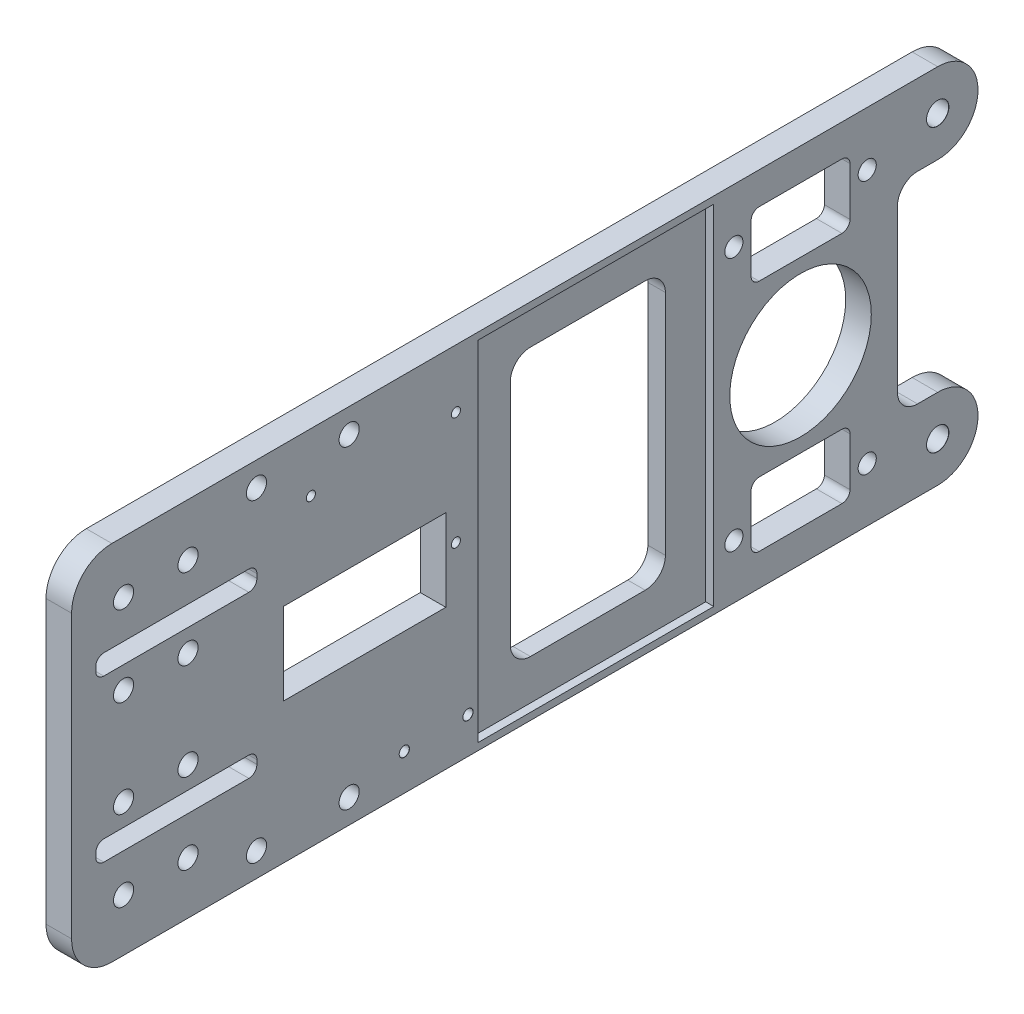
SolidWorks part; units mm, degrees
other "Chassis"
other "Bearing Plate"
other "IMU"
other "Bearing Plate 2"
material "Nylon 101"
ref_plane "Front Plane" through (0, 0, 0) normal (1, 0, 0) x (0, 1, 0)
ref_plane "Top Plane" through (0, 0, 0) normal (0, 0, 1) x (0, 1, 0)
ref_plane "Right Plane" through (0, 0, 0) normal (0, 1, 0) x (-1, 0, 0)
sketch "Sketch1" plane through (0, 0, 0) normal (1, 0, 0) x (0, 1, 0)
  line L0 (-45, 121.55) -> (-45, -44.05)
  line L1 (-45, -44.05) -> (45, -44.05)
  line L2 (45, -44.05) -> (45, 121.55)
  line L5 (0, 180.95) -> (0, 0) construction
  line L6 (-45, 121.55) -> (0, 121.55) construction
  line L7 (0, 121.55) -> (45, 121.55) construction
  line L8 (-448.1018, -246.5596) -> (346.2414, -246.5596) construction
  line L9 (0, 77.55) -> (0, 121.55) construction
  line L10 (-40.75, 77.55) -> (40.75, 77.55)
  line L11 (-40.75, 77.55) -> (-40.75, 24.05)
  line L12 (-40.75, 24.05) -> (40.75, 24.05)
  line L13 (40.75, 77.55) -> (40.75, 24.05)
  line L14 (-35, -34.05) -> (35, -34.05) construction
  line L15 (-35, -24.05) -> (35, -24.05)
  line L16 (-35, -44.05) -> (35, -44.05)
  line L17 (0, -34.05) -> (0, 0) construction
  line L18 (-36, 98.35) -> (-36, 82.55) construction
  line L19 (-33.525, 100.825) -> (-33.525, 80.075)
  line L20 (-33.525, 100.825) -> (-49.025, 100.825)
  line L21 (-49.025, 100.825) -> (-49.025, 80.075)
  line L22 (-33.525, 80.075) -> (-49.025, 80.075)
  line L23 (-36, 90.45) -> (-49.025, 90.45) construction
  line L24 (-36, 100.825) -> (-36, 98.35) construction
  line L25 (-36, 98.35) -> (-33.525, 98.35) construction
  line L26 (-33.525, 80.075) -> (-33.525, 77.55) construction
  line L27 (0, 103.55) -> (2.5, 103.55) construction
  line L36 (0, 124.55) -> (33, 124.55)
  line L37 (0, 124.55) -> (0, 82.55)
  line L38 (0, 82.55) -> (33, 82.55)
  line L39 (33, 124.55) -> (33, 82.55)
  line L40 (2.5, 121.55) -> (30.5, 121.55) construction
  line L41 (2.5, 121.55) -> (2.5, 85.55) construction
  line L42 (2.5, 85.55) -> (30.5, 85.55) construction
  line L43 (30.5, 121.55) -> (30.5, 85.55) construction
  line L44 (16.5, 121.55) -> (16.5, 124.55) construction
  line L45 (-45, 180.95) -> (-45, 121.55)
  line L46 (0, 180.95) -> (-45, 180.95)
  line L47 (0, 180.95) -> (45, 180.95)
  line L48 (45, 180.95) -> (45, 121.55)
  circle A0 centre (0, 0) radius 6.35 construction
  circle A1 centre (0, 0) radius 17.4625 construction
  circle A2 centre (0, 0) radius 19.05 construction
  circle A3 centre (0, 0) radius 17.5641
  arc A4 (-35, -24.05) -> (-35, -44.05) centre (-35, -34.05) ccw
  arc A5 (35, -44.05) -> (35, -24.05) centre (35, -34.05) ccw
  circle A6 centre (-36, 98.35) radius 1.5
  circle A7 centre (-36, 82.55) radius 1.5
  point P22 (0, -34.05)
  dimension "D5" = 12.7
  dimension "D6" = 34.925
  dimension "D8" = 38.1
  dimension "D9" = 0.1016
  dimension "D10" = 35.1282
  dimension "D14" = 10
  dimension "D3" = 5
  dimension "D15" = 5
  dimension "D18" = 3
  dimension "D20" = 7.5
  dimension "D25" = 28
  dimension "D27" = 5
  dimension "D28" = 12
  dimension "D29" = 5
  dimension "D4" = 90
  dimension "D7" = 246.5596
  dimension "D11" = 81.5
  dimension "D12" = 53.5
  dimension "D16" = 15.5
  dimension "D17" = 20.75
  dimension "D19" = 15.8
  dimension "D22" = 225
  dimension "D23" = 33
  dimension "D24" = 42
  dimension "D26" = 36
extrude "Boss-Extrude1" add sketch "Sketch1" along normal mid plane 6.35
sketch "Sketch2" plane through (3.175, 0, 0) normal (1, 0, 0) x (0, 1, 0)
  line L0 (-39.05, 0) -> (-19.05, 0) construction
  line L1 (-39.05, 21.55) -> (39.05, 21.55)
  line L2 (-39.05, 21.55) -> (-39.05, -21.55)
  line L3 (-39.05, -21.55) -> (39.05, -21.55)
  line L4 (39.05, 21.55) -> (39.05, -21.55)
  line L5 (19.05, 0) -> (39.05, 0) construction
  line L6 (-31.55, 16.55) -> (31.55, 16.55) construction
  line L7 (31.55, 16.55) -> (31.55, -16.55) construction
  line L8 (31.55, -16.55) -> (-31.55, -16.55) construction
  line L9 (-31.55, -16.55) -> (-31.55, 16.55) construction
  line L10 (0, 16.55) -> (0, 21.55) construction
  line L11 (31.55, 0) -> (39.05, 0) construction
  line L12 (-31.55, 24.05) -> (-31.55, 16.55) construction
  line L13 (-31.55, 16.55) -> (-39.05, 16.55) construction
  line L14 (-40.75, 24.05) -> (40.75, 24.05) construction
  circle A1 centre (0, 0) radius 19.05 construction
  circle A2 centre (-31.55, 16.55) radius 2 construction
  circle A3 centre (-31.55, -16.55) radius 2 construction
  circle A4 centre (31.55, 16.55) radius 2 construction
  circle A5 centre (31.55, -16.55) radius 2 construction
  dimension "D1" = 20
  dimension "D3" = 4
  dimension "D2" = 7.5
  dimension "D4" = 2.5
extrude "Boss-Extrude2" add sketch "Sketch2" along normal blind 8.7312 separate body
sketch "Sketch3" plane through (11.9062, 0, 0) normal (1, 0, 0) x (0, 1, 0)
  circle A0 centre (0, 0) radius 17.5641 construction
  circle A1 centre (0, 0) radius 17.5641
hole_wizard "M4 Clearance Hole2" positions "Sketch22" profile "Sketch23" hole size "M4" standard "ANSI Metric" end condition through all
sketch "Sketch22" plane through (11.9062, 0, 0) normal (1, 0, 0) x (0, 1, 0)
  point P0 (-31.55, 16.55)
  point P3 (-31.55, -16.55)
  point P6 (31.55, -16.55)
  point P9 (31.55, 16.55)
sketch "Sketch23" plane through (11.9062, -31.55, 16.55) normal (0, 1, 0) x (0, 0, -1)
  line L0 (0, 0) -> (0, 15.0813)
  line L1 (0, 15.0813) -> (2.25, 15.0813)
  line L2 (2.25, 15.0813) -> (2.25, 0.025)
  line L3 (2.25, 0.025) -> (2.275, 0)
  line L5 (2.275, 0) -> (0, 0)
  line L6 (-2.25, 0.025) -> (-2.275, 0) construction
  line L11 (0, -6.35) -> (0, 107.95) construction
  dimension "Thru Hole Dia." = 4.5
  dimension "Thru Hole Depth" = 15.0813
  dimension "Near C'Sink Dia." = 4.55
  dimension "Near C'Sink Angle" = 90
sketch "Sketch24" plane through (-3.175, 0, 0) normal (-1, 0, 0) x (0, -1, 0)
  line L0 (39.05, 21.55) -> (39.05, -21.55) construction
  line L1 (39.05, -21.55) -> (-39.05, -21.55) construction
  line L2 (-39.05, 21.55) -> (-39.05, -21.55) construction
  line L3 (39.05, 21.55) -> (-39.05, 21.55) construction
  line L4 (39.05, 21.55) -> (39.05, -21.55)
  line L5 (39.05, -21.55) -> (-39.05, -21.55)
  line L6 (-39.05, 21.55) -> (-39.05, -21.55)
  line L7 (39.05, 21.55) -> (-39.05, 21.55)
extrude "Boss-Extrude3" add sketch "Sketch24" along normal blind 8.7312 separate body
hole_wizard "Tap Drill for M4x0.7 Tap1" positions "Sketch25" profile "Sketch27" hole size "M4x0.7" standard "ANSI Metric"
sketch "Sketch25" plane through (-11.9062, 0, 0) normal (-1, 0, 0) x (0, -1, 0)
  point P0 (-31.55, 16.55)
  point P2 (-31.55, -16.55)
  point P4 (31.55, -16.55)
  point P6 (31.55, 16.55)
sketch "Sketch27" plane through (-11.9062, 31.55, 16.55) normal (0, 1, 0) x (0, 0, 1)
  line L0 (0, 0) -> (0, 9.7227)
  line L1 (0, 9.7227) -> (1.65, 8.7312)
  line L2 (1.65, 8.7312) -> (1.65, 0.025)
  line L3 (1.65, 0.025) -> (1.675, 0)
  line L5 (1.675, 0) -> (0, 0)
  line L6 (-1.65, 0.025) -> (-1.675, 0) construction
  line L10 (0, 9.7227) -> (-1.65, 8.7312) construction
  line L11 (0, -6.35) -> (0, 107.95) construction
  dimension "Hole Dia." = 3.3
  dimension "Hole Depth" = 8.7312
  dimension "Near C'Sink Dia." = 3.35
  dimension "Near C'Sink Angle" = 90
  dimension "Drill Angle" = 118
hole_wizard "Tap Drill for M3x0.5 Tap1" positions "Sketch9" profile "Sketch10" hole size "M3x0.5" standard "ANSI Metric" end condition through all
sketch "Sketch9" plane through (3.175, 0, 0) normal (1, 0, 0) x (0, 1, 0)
  point P0 (-36, 98.35)
  point P3 (-36, 82.55)
sketch "Sketch10" plane through (3.175, -36, 98.35) normal (0, 1, 0) x (0, 0, -1)
  line L0 (0, 0) -> (0, 15.0813)
  line L1 (0, 15.0813) -> (1.25, 15.0813)
  line L2 (1.25, 15.0813) -> (1.25, 0.025)
  line L3 (1.25, 0.025) -> (1.275, 0)
  line L5 (1.275, 0) -> (0, 0)
  line L6 (-1.25, 0.025) -> (-1.275, 0) construction
  line L11 (0, -6.35) -> (0, 107.95) construction
  dimension "Thru Hole Dia." = 2.5
  dimension "Thru Hole Depth" = 15.0813
  dimension "Near C'Sink Dia." = 2.55
  dimension "Near C'Sink Angle" = 90
extrude "Cut-Extrude3" cut sketch "Sketch3" against normal through all
hole_wizard "M5 Clearance Hole1" positions "Sketch13" profile "Sketch12" hole size "M5" standard "ANSI Metric" end condition through all
sketch "Sketch13" plane through (3.175, 0, 0) normal (1, 0, 0) x (0, 1, 0)
  point P0 (-35, -34.05)
  point P3 (35, -34.05)
sketch "Sketch12" plane through (3.175, -35, -34.05) normal (0, 1, 0) x (0, 0, -1)
  line L0 (0, 0) -> (0, 15.0813)
  line L1 (0, 15.0813) -> (2.75, 15.0813)
  line L2 (2.75, 15.0813) -> (2.75, 0.025)
  line L3 (2.75, 0.025) -> (2.775, 0)
  line L5 (2.775, 0) -> (0, 0)
  line L6 (-2.75, 0.025) -> (-2.775, 0) construction
  line L11 (0, -6.35) -> (0, 107.95) construction
  dimension "Thru Hole Dia." = 5.5
  dimension "Thru Hole Depth" = 15.0813
  dimension "Near C'Sink Dia." = 5.55
  dimension "Near C'Sink Angle" = 90
sketch "Sketch14" plane through (3.175, 0, 0) normal (1, 0, 0) x (0, 1, 0)
  line L8 (43.25, 21.55) -> (43.25, 80.05)
  line L9 (-43.25, 21.55) -> (43.25, 21.55)
  line L10 (-43.25, 80.05) -> (-43.25, 21.55)
  line L11 (43.25, 80.05) -> (-43.25, 80.05)
  line L12 (43.25, 21.55) -> (43.25, 80.05)
  line L13 (-43.25, 21.55) -> (43.25, 21.55)
  line L14 (-43.25, 80.05) -> (-43.25, 21.55)
  line L15 (43.25, 80.05) -> (-43.25, 80.05)
  dimension "D1" = 2.5
extrude "Cut-Extrude4" cut sketch "Sketch14" against normal blind 2
fillet "Fillet4" radius 10 4 edges at (0, 45, -44.05) (0, -45, -44.05) (0, 45, 180.95) (0, -45, 180.95)
fillet "Fillet5" radius 5 4 edges at (-7.5406, -39.05, 21.55) (-7.5406, -39.05, -21.55) (-7.5406, 39.05, -21.55) (-7.5406, 39.05, 21.55)
fillet "Fillet6" radius 5 4 edges at (7.5406, -39.05, 21.55) (7.5406, 39.05, -21.55) (7.5406, -39.05, -21.55) (7.5406, 39.05, 21.55)
sketch "Sketch28" plane through (3.175, 0, 0) normal (1, 0, 0) x (0, 1, 0)
  line L0 (-33.525, 100.825) -> (-49.025, 100.825) construction
  line L1 (-33.525, 100.825) -> (-49.025, 100.825)
  line L2 (-49.025, 100.825) -> (-49.025, 80.075) construction
  line L3 (-49.025, 100.825) -> (-49.025, 80.075)
  line L4 (-33.525, 100.825) -> (-33.525, 80.075) construction
  line L5 (-33.525, 100.825) -> (-33.525, 80.075)
  line L6 (-33.525, 80.075) -> (-49.025, 80.075) construction
  line L7 (-33.525, 80.075) -> (-49.025, 80.075)
  circle A0 centre (-36, 82.55) radius 1.5 construction
  circle A1 centre (-36, 82.55) radius 1.5
  circle A2 centre (-36, 98.35) radius 1.5 construction
  circle A3 centre (-36, 98.35) radius 1.5
extrude "Boss-Extrude4" add sketch "Sketch28" along normal blind 2.5 separate body
fillet "Fillet7" radius 1 4 edges at (4.425, -33.525, 100.825) (4.425, -33.525, 80.075) (4.425, -49.025, 80.075) (4.425, -49.025, 100.825)
sketch "Sketch29" plane through (3.175, 0, 0) normal (-1, 0, 0) x (0, -1, 0)
  line L0 (47.025, 100.825) -> (47.025, 80.075) construction
  line L1 (47.025, 90.45) -> (49.025, 90.45) construction
  line L3 (48.025, 80.075) -> (34.525, 80.075) construction
  line L4 (49.025, 99.825) -> (49.025, 81.075) construction
  line L6 (47.025, 80.2) -> (47.025, 80.075) construction
  line L8 (47.025, 100.825) -> (47.025, 100.7) construction
  circle A6 centre (47.025, 99.2) radius 1.5
  circle A7 centre (47.025, 95.7) radius 1.5
  circle A8 centre (47.025, 92.2) radius 1.5
  circle A9 centre (47.025, 88.7) radius 1.5
  circle A10 centre (47.025, 85.2) radius 1.5
  circle A11 centre (47.025, 81.7) radius 1.5
  dimension "D3" = 6
  dimension "D2" = 3
  dimension "D4" = 0.5
  dimension "D1" = 2
extrude "Boss-Extrude5" add sketch "Sketch29" along normal blind 1.5
fillet "Fillet8" radius 0.5 6 edges at (1.675, -47.025, 83.2) (1.675, -47.025, 86.7) (1.675, -47.025, 90.2) (1.675, -47.025, 93.7) (1.675, -47.025, 97.2) (1.675, -47.025, 100.7)
hole_wizard "Tap Drill for #4-40 Tap1" positions "Sketch33" profile "Sketch34" hole size "#4-40" standard "ANSI Inch" end condition through all
sketch "Sketch33" plane through (3.175, 0, 0) normal (1, 0, 0) x (0, 1, 0)
  point P0 (2.5, 121.55)
  point P3 (2.5, 85.55)
  point P6 (30.5, 85.55)
  point P9 (30.5, 121.55)
  point P12 (0, 0)
sketch "Sketch34" plane through (3.175, 2.5, 121.55) normal (0, 1, 0) x (0, 0, -1)
  line L0 (0, 0) -> (0, 15.0813)
  line L1 (0, 15.0813) -> (1.1303, 15.0813)
  line L2 (1.1303, 15.0813) -> (1.1303, 0)
  line L5 (1.1303, 0) -> (0, 0)
  line L11 (0, -6.35) -> (0, 107.95) construction
  dimension "Thru Hole Dia." = 2.2606
  dimension "Thru Hole Depth" = 15.0813
sketch "Sketch36" plane through (11.9062, 0, 0) normal (1, 0, 0) x (0, 1, 0)
  line L0 (-39.05, 16.55) -> (-39.05, -16.55) construction
  line L1 (-37.05, 12.275) -> (-21.05, 12.275)
  line L2 (-37.05, 12.275) -> (-37.05, -12.275)
  line L3 (-37.05, -12.275) -> (-21.05, -12.275)
  line L4 (-21.05, 12.275) -> (-21.05, -12.275)
  line L5 (0, 0) -> (0, 21.55) construction
  line L6 (34.05, 21.55) -> (-34.05, 21.55) construction
  line L7 (21.05, 12.275) -> (21.05, -12.275)
  line L8 (37.05, -12.275) -> (21.05, -12.275)
  line L9 (37.05, 12.275) -> (37.05, -12.275)
  line L10 (37.05, 12.275) -> (21.05, 12.275)
  circle A1 centre (0, 0) radius 19.05 construction
  circle A3 centre (-31.55, 16.55) radius 2.275 construction
  circle A5 centre (-31.55, -16.55) radius 2.275 construction
  dimension "D1" = 2
  dimension "D2" = 2
  dimension "D3" = 2
  dimension "D4" = 2
extrude "Cut-Extrude6" cut sketch "Sketch36" against normal through all
fillet "Fillet9" radius 2 8 edges at (7.5406, -37.05, 12.275) (7.5406, 21.05, -12.275) (7.5406, 37.05, -12.275) (7.5406, 37.05, 12.275) (7.5406, 21.05, 12.275) (7.5406, -21.05, -12.275) (7.5406, -37.05, -12.275) (7.5406, -21.05, 12.275)
fillet "Fillet10" radius 2 8 edges at (-7.5406, -21.05, 12.275) (-7.5406, -21.05, -12.275) (-7.5406, -37.05, -12.275) (-7.5406, -37.05, 12.275) (-7.5406, 37.05, -12.275) (-7.5406, 21.05, -12.275) (-7.5406, 21.05, 12.275) (-7.5406, 37.05, 12.275)
sketch "Sketch37" plane through (3.175, 0, 0) normal (1, 0, 0) x (0, 1, 0)
  line L0 (0, 180.95) -> (0, -44.05) construction
  line L1 (-35, 180.95) -> (35, 180.95) construction
  line L2 (-35, -44.05) -> (35, -44.05) construction
  line L4 (-20.5, 174.95) -> (-19.5, 174.95)
  line L5 (-22.5, 172.95) -> (-22.5, 136.95)
  line L6 (-20.5, 134.95) -> (-19.5, 134.95)
  line L7 (-17.5, 172.95) -> (-17.5, 136.95)
  line L8 (17.5, 172.95) -> (17.5, 136.95)
  line L9 (20.5, 134.95) -> (19.5, 134.95)
  line L10 (22.5, 172.95) -> (22.5, 136.95)
  line L11 (20.5, 174.95) -> (19.5, 174.95)
  arc A0 (-22.5, 136.95) -> (-20.5, 134.95) centre (-20.5, 136.95) ccw
  arc A1 (-19.5, 134.95) -> (-17.5, 136.95) centre (-19.5, 136.95) ccw
  arc A2 (-19.5, 174.95) -> (-17.5, 172.95) centre (-19.5, 172.95) cw
  arc A3 (-20.5, 174.95) -> (-22.5, 172.95) centre (-20.5, 172.95) ccw
  arc A4 (20.5, 174.95) -> (22.5, 172.95) centre (20.5, 172.95) cw
  arc A5 (19.5, 174.95) -> (17.5, 172.95) centre (19.5, 172.95) ccw
  arc A6 (19.5, 134.95) -> (17.5, 136.95) centre (19.5, 136.95) cw
  arc A7 (22.5, 136.95) -> (20.5, 134.95) centre (20.5, 136.95) cw
  point P10 (-20, 174.95)
  point P15 (-22.5, 134.95)
  point P18 (-17.5, 134.95)
  point P21 (-17.5, 174.95)
  point P36 (17.5, 174.95)
  point P37 (17.5, 134.95)
  point P38 (22.5, 134.95)
  dimension "D5" = 2
  dimension "D1" = 5
  dimension "D2" = 40
  dimension "D3" = 20
  dimension "D4" = 6
extrude "Cut-Extrude7" cut sketch "Sketch37" against normal through all both and the other way through all
sketch "Sketch38" plane through (3.175, 0, 0) normal (1, 0, 0) x (0, 1, 0)
  line L0 (43.25, 80.05) -> (-43.25, 80.05) construction
  line L1 (-28.25, 31.55) -> (28.25, 31.55)
  line L2 (-33.25, 36.55) -> (-33.25, 65.05)
  line L3 (-28.25, 70.05) -> (28.25, 70.05)
  line L4 (33.25, 36.55) -> (33.25, 65.05)
  line L5 (-43.25, 80.05) -> (-43.25, 21.55) construction
  line L6 (-43.25, 21.55) -> (43.25, 21.55) construction
  line L7 (-35, -44.05) -> (35, -44.05) construction
  line L8 (-20, -24.05) -> (20, -24.05)
  line L9 (-25, -29.05) -> (-25, -34.05)
  line L10 (-25, -44.05) -> (25, -44.05)
  line L12 (-25, -24.05) -> (0, -34.05) construction
  line L13 (-25, -44.05) -> (0, -34.05) construction
  line L14 (-35, -44.05) -> (35, -44.05)
  line L15 (0, -24.05) -> (0, -44.05)
  line L16 (25, -29.05) -> (25, -34.05)
  arc A0 (28.25, 70.05) -> (33.25, 65.05) centre (28.25, 65.05) cw
  arc A1 (28.25, 31.55) -> (33.25, 36.55) centre (28.25, 36.55) ccw
  arc A2 (-28.25, 31.55) -> (-33.25, 36.55) centre (-28.25, 36.55) cw
  arc A3 (-33.25, 65.05) -> (-28.25, 70.05) centre (-28.25, 65.05) cw
  circle A4 centre (35, -34.05) radius 2.775 construction
  circle A5 centre (-35, -34.05) radius 2.775 construction
  circle A6 centre (35, -34.05) radius 2.775
  circle A7 centre (-35, -34.05) radius 2.775
  arc A8 (-35, -44.05) -> (-25, -34.05) centre (-35, -34.05) ccw
  arc A9 (-20, -24.05) -> (-25, -29.05) centre (-20, -29.05) ccw
  arc A10 (35, -44.05) -> (25, -34.05) centre (35, -34.05) cw
  arc A11 (20, -24.05) -> (25, -29.05) centre (20, -29.05) cw
  point P5 (0, 31.55)
  point P21 (0, -34.05)
  point P28 (0, 0)
  point P38 (0, -34.05)
  line M67 (-35, -44.05) -> (35, -44.05)
  dimension "D3" = 5
  dimension "D6" = 5
  dimension "D1" = 10
  dimension "D2" = 10
  dimension "D4" = 10
  dimension "D5" = 20
extrude "Cut-Extrude8" cut sketch "Sketch38" against normal through all contours A3 L2 A2 L1 A1 L4 A0 L3 | A11 L8 L15 L14 A10 L16 M67 | L8 A9 L9 A8 L15 M67
sketch "Sketch39" plane through (3.175, 0, 0) normal (1, 0, 0) x (0, 1, 0)
  line L0 (-35, 180.95) -> (35, 180.95) construction
  line L1 (-35, 180.95) -> (35, 180.95) construction
  line L2 (0, 0) -> (0, 180.95) construction
  line L3 (43.25, 80.05) -> (-43.25, 80.05) construction
  line L4 (43.25, 80.05) -> (-43.25, 80.05) construction
  line L5 (45, -34.05) -> (45, 170.95) construction
  circle A0 centre (39, 112.05) radius 2.5
  circle A1 centre (32, 168.05) radius 2.5
  circle A2 centre (32, 152.05) radius 2.5
  circle A3 centre (12, 168.05) radius 2.5
  circle A4 centre (12, 152.05) radius 2.5
  circle A5 centre (39, 135.05) radius 2.5
  circle A6 centre (-39, 135.05) radius 2.5
  circle A7 centre (-12, 152.05) radius 2.5
  circle A8 centre (-12, 168.05) radius 2.5
  circle A9 centre (-32, 152.05) radius 2.5
  circle A10 centre (-32, 168.05) radius 2.5
  circle A11 centre (-39, 112.05) radius 2.5
  dimension "D1" = 5
  dimension "D2" = 5
  dimension "D3" = 5
  dimension "D4" = 5
  dimension "D5" = 5
  dimension "D6" = 5
  dimension "D7" = 32
  dimension "D8" = 55
  dimension "D9" = 72
  dimension "D10" = 88
  dimension "D11" = 20
  dimension "D12" = 12
  dimension "D13" = 6
extrude "Cut-Extrude9" cut sketch "Sketch39" against normal through all
sketch "Sketch40" plane through (3.175, 0, 0) normal (1, 0, 0) x (0, 0, -1)
  line L0 (-80.05, 43.25) -> (-80.05, -43.25) construction
  line L1 (-128.4, -10.175) -> (-88.05, -10.175)
  line L2 (-128.4, -10.175) -> (-128.4, 10.175)
  line L3 (-128.4, 10.175) -> (-88.05, 10.175)
  line L4 (-88.05, -10.175) -> (-88.05, 10.175)
  point P4 (-88.05, 0)
  dimension "D1" = 20.35
  dimension "D2" = 40.35
  dimension "D3" = 8
extrude "Cut-Extrude10" cut sketch "Sketch40" against normal through all
delete or keep bodies "Body-Delete/Keep 1" type keep bodies bodies 142
fillet "Fillet11" radius 2 8 edges at (0, 37.05, -12.275) (0, 21.05, -12.275) (0, 37.05, 12.275) (0, 21.05, 12.275) (0, -21.05, 12.275) (0, -21.05, -12.275) (0, -37.05, -12.275) (0, -37.05, 12.275)
sketch "Sketch42" plane through (-3.175, 0, 0) normal (1, 0, 0) x (0, 1, 0)
  line L0 (10.175, 88.05) -> (10.175, 128.4) construction
  line L1 (-12.175, 130.4) -> (12.175, 130.4)
  line L2 (-12.175, 130.4) -> (-12.175, 126.4)
  line L3 (-12.175, 126.4) -> (-10.175, 126.4)
  line L4 (12.175, 130.4) -> (12.175, 126.4)
  line L5 (10.175, 128.4) -> (-10.175, 128.4) construction
  line L6 (-10.175, 128.4) -> (-10.175, 88.05) construction
  line L7 (10.175, 126.4) -> (10.175, 128.4)
  line L8 (10.175, 128.4) -> (-10.175, 128.4)
  line L9 (-10.175, 128.4) -> (-10.175, 126.4)
  line L10 (10.175, 126.4) -> (12.175, 126.4)
  point P4 (-13.0811, 132.809)
  dimension "D1" = 2
  dimension "D2" = 2
  dimension "D3" = 2
  dimension "D4" = 2
extrude "Boss-Extrude6" add sketch "Sketch42" against normal blind 12
sketch "Sketch43" plane through (-15.175, 0, 0) normal (-1, 0, 0) x (0, -1, 0)
  line L1 (10.175, 128.4) -> (-10.175, 128.4)
  line L2 (10.175, 128.4) -> (10.175, 126.4)
  line L3 (10.175, 126.4) -> (-10.175, 126.4)
  line L4 (-10.175, 128.4) -> (-10.175, 126.4)
extrude "Boss-Extrude7" add sketch "Sketch43" against normal blind 2
